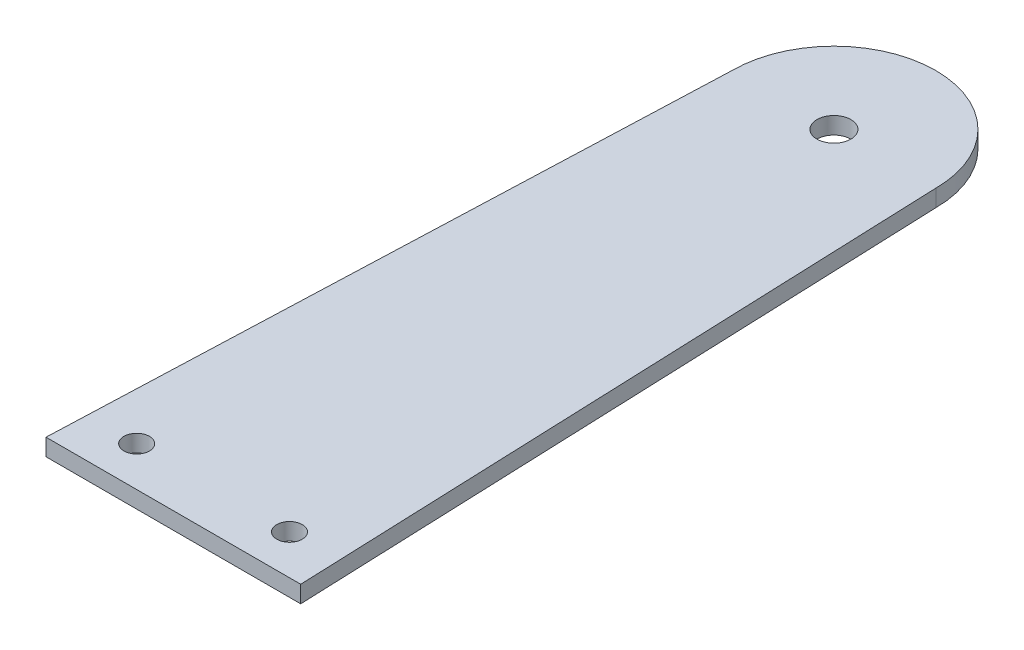
SolidWorks part; units mm, degrees
ref_plane "Спереди" through (0, 0, 0) normal (0, 0, 1) x (1, 0, 0)
ref_plane "Сверху" through (0, 0, 0) normal (0, 1, 0) x (1, 0, 0)
ref_plane "Справа" through (0, 0, 0) normal (1, 0, 0) x (0, 0, -1)
sketch "Эскиз1" plane through (0, 0, 0) normal (0, 1, 0) x (1, 0, 0)
  line L0 (-17.6252, -24.9379) -> (12.3748, -24.9379) construction
  line L1 (-17.6252, -29.6173) -> (12.3748, -29.6173)
  line L2 (-17.6252, -29.6173) -> (-17.6252, 48.1827) construction
  line L3 (-17.6252, 52.3827) -> (12.3748, 52.3827) construction
  line L5 (-11.6252, -26.4379) -> (6.3748, -26.4379) construction
  line L6 (-2.6252, -29.6173) -> (-2.6252, 60.301) construction
  line L7 (-14.6252, 48.1827) -> (-17.6252, -29.6173)
  line L8 (9.3748, 48.1827) -> (12.3748, -29.6173)
  circle A0 centre (-11.6252, -24.9379) radius 1.5
  circle A1 centre (6.3748, -24.9379) radius 1.5
  circle A2 centre (-2.6252, 48.1827) radius 2
  arc A3 (9.3748, 48.1827) -> (-14.6252, 48.1827) centre (-2.6252, 48.1827) ccw
  dimension "D3" = 77.8
  dimension "D4" = 4
  dimension "D7" = 3
  dimension "D2" = 30
  dimension "D5" = 18
  dimension "D6" = 6
extrude "Бобышка-Вытянуть1" add sketch "Эскиз1" along normal blind 2
